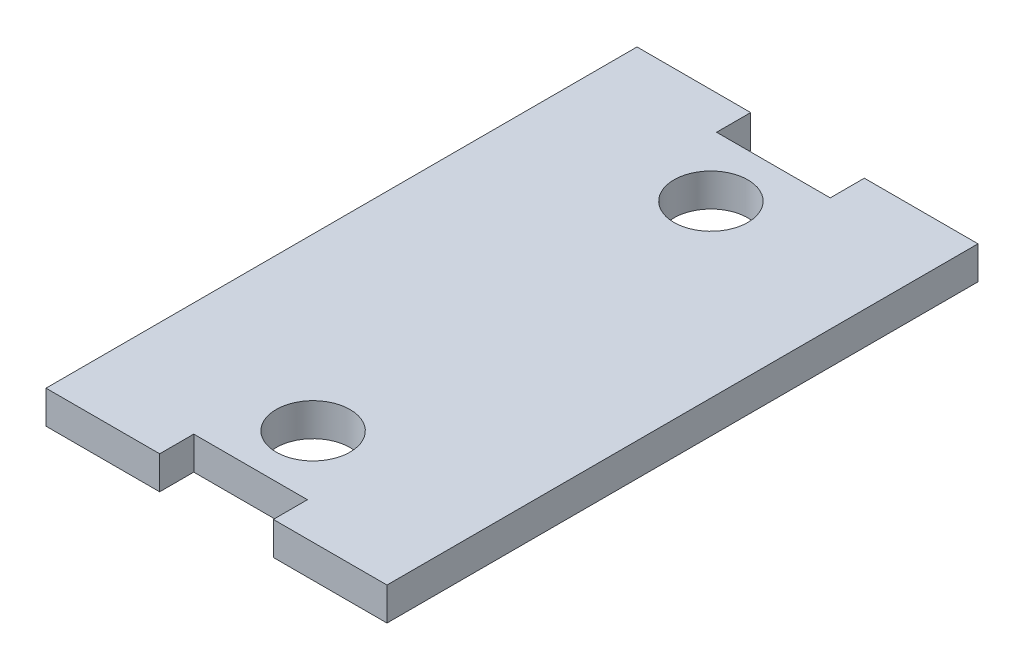
SolidWorks part; units mm, degrees
ref_plane "Front" through (0, 0, 0) normal (0, 0, 1) x (1, 0, 0)
ref_plane "Top" through (0, 0, 0) normal (0, 1, 0) x (1, 0, 0)
ref_plane "Right" through (0, 0, 0) normal (1, 0, 0) x (0, 0, -1)
sketch "Sketch1" plane through (0, 0, 0) normal (0, 1, 0) x (1, 0, 0)
  line L0 (-11.4489, 0) -> (16.6876, 0) construction
  line L1 (-7.5, 13) -> (-2.5, 13)
  line L2 (-7.5, 13) -> (-7.5, -13)
  line L3 (-7.5, -13) -> (-2.5, -13)
  line L4 (7.5, 13) -> (7.5, -13)
  line L5 (-7.5, 13) -> (7.5, -13) construction
  line L6 (-7.5, -13) -> (7.5, 13) construction
  line L7 (2.5, 11.5) -> (-2.5, 11.5)
  line L8 (2.5, 11.5) -> (2.5, 13)
  line L10 (-2.5, 11.5) -> (-2.5, 13)
  line L11 (2.5, 11.5) -> (-2.5, 13) construction
  line L12 (2.5, 13) -> (-2.5, 11.5) construction
  line L13 (2.5, -13) -> (-2.5, -11.5) construction
  line L14 (2.5, -11.5) -> (-2.5, -13) construction
  line L15 (-2.5, -11.5) -> (-2.5, -13)
  line L17 (2.5, -11.5) -> (2.5, -13)
  line L18 (2.5, -11.5) -> (-2.5, -11.5)
  line L19 (2.5, -13) -> (7.5, -13)
  line L20 (2.5, 13) -> (7.5, 13)
  circle A0 centre (0, 8.75) radius 1.625
  circle A1 centre (0, -8.75) radius 1.625
  point P0 (0, 0)
  point P6 (0, 12.25)
  point P17 (0, -12.25)
  dimension "D5" = 3.25
  dimension "D1" = 15
  dimension "D2" = 26
  dimension "D3" = 5
  dimension "D4" = 1.5
  dimension "D6" = 17.5
extrude "Boss-Extrude1" add sketch "Sketch1" along normal blind 1.45
